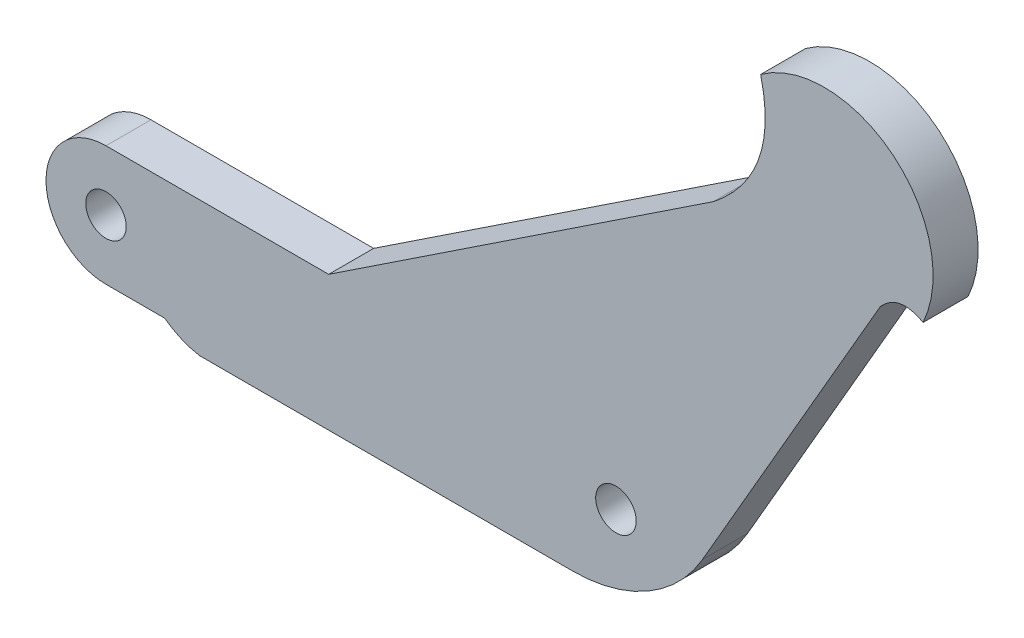
SolidWorks part; units mm, degrees
ref_plane "前视基准面" through (0, 0, 0) normal (0, 0, 1) x (1, 0, 0)
ref_plane "上视基准面" through (0, 0, 0) normal (0, 1, 0) x (1, 0, 0)
ref_plane "右视基准面" through (0, 0, 0) normal (1, 0, 0) x (0, 0, -1)
sketch "草图1" plane through (0, 0, 0) normal (0, 0, 1) x (1, 0, 0)
  line L0 (0, 0) -> (34, 0) construction
  line L1 (34, 0) -> (51.5, 30.3109) construction
  line L2 (6.2261, -5) -> (31.1132, -5)
  line L3 (39.7735, 0) -> (51.6229, 20.5237)
  line L4 (0, -4) -> (3.9083, -4)
  line L5 (0, 4) -> (14.8469, 4)
  line L6 (14.8469, 4) -> (40.4719, 21.0059)
  arc A3 (39.7735, 0) -> (31.1132, -5) centre (31.1132, 5) cw
  arc A4 (0, 4) -> (0, -4) centre (0, 0) ccw
  arc A5 (43.6473, 29.9426) -> (54.4752, 21.0327) centre (47.9018, 24.0786) cw
  circle A7 centre (0, 0) radius 1.35
  circle A8 centre (34, 0) radius 1.35
  spline S0 degree 2 poles (3.9083, -4) (4.9486, -4.7674) (6.2261, -5) knots 0 0 0 1 1 1
  spline S1 degree 2 poles (51.6229, 20.5237) (52.8722, 21.9254) (54.4752, 21.0327) knots 0 0 0 1 1 1
  spline S2 degree 2 poles (40.4719, 21.0059) (44.9825, 24.5269) (43.6473, 29.9426) knots 0 0 0 1 1 1
  dimension "D1" = 2.7
  dimension "D2" = 34
  dimension "D5" = 8
  dimension "D7" = 10
  dimension "D8" = 120
  dimension "D3" = 5
  dimension "D4" = 35
  dimension "D6" = 5
extrude "凸台-拉伸2" add sketch "草图1" along normal blind 3
